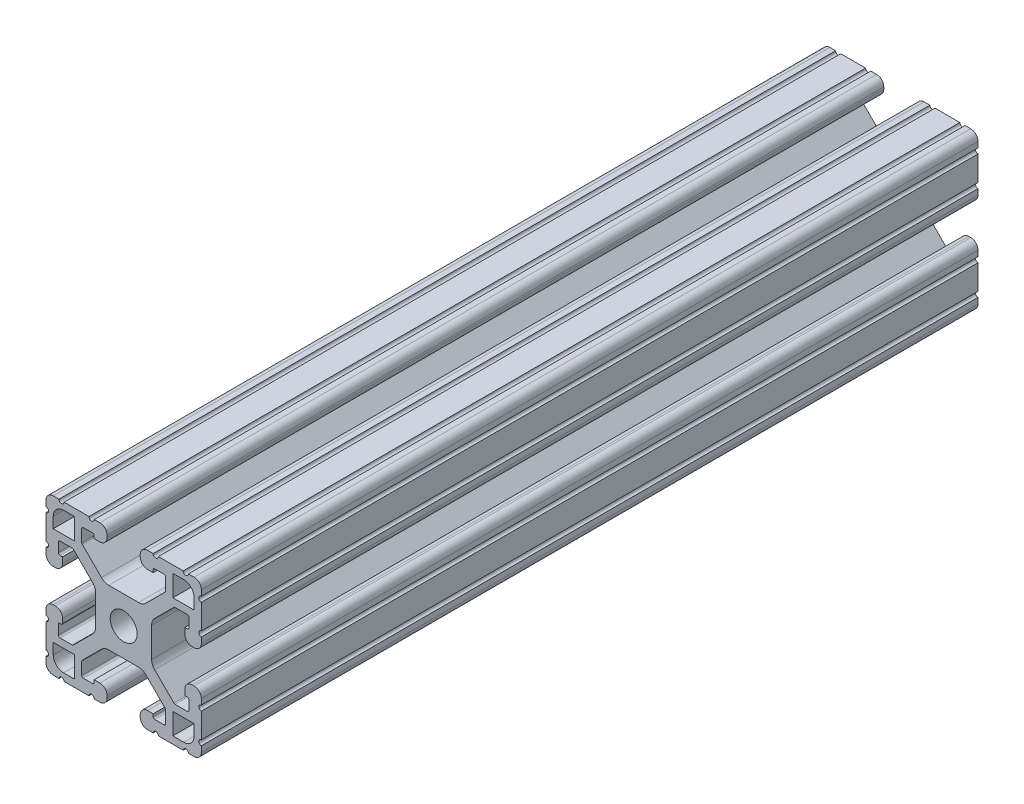
SolidWorks part; units mm, degrees
ref_plane "Front Plane" through (0, 0, 0) normal (0, 0, 1) x (1, 0, 0)
ref_plane "Top Plane" through (0, 0, 0) normal (0, 1, 0) x (1, 0, 0)
ref_plane "Right Plane" through (0, 0, 0) normal (1, 0, 0) x (0, 0, -1)
sketch "Sketch1" plane through (0, 0, 0) normal (0, 0, 1) x (1, 0, 0)
  line L0 (0, -19.05) -> (0, 19.05) construction
  line L1 (19.05, 0) -> (-19.05, 0) construction
  line L2 (4.064, 19.05) -> (-4.064, 19.05) construction
  line L3 (0, -6.858) -> (0, 6.858) construction
  line L4 (-4.064, 19.05) -> (-4.064, 14.986) construction
  line L5 (19.05, -10.287) -> (19.05, 10.287) construction
  line L6 (0, -3.302) -> (0, 3.302) construction
  point P4 (0, 0)
  point P8 (0, 0)
  point P11 (0, 19.05)
  point P14 (0, 0)
  point P18 (19.05, 0)
  point P21 (0, 0)
  dimension "Rail Width" = 38.1
  dimension "Rail Height" = 38.1
  dimension "T-Slot Width" = 8.128
  dimension "Thickness" = 4.064
  dimension "Opening Width" = 20.574
  dimension "Center Hole Diameter" = 6.604
  dimension "Slot Depth" = 12.192
sketch "Sketch2" plane through (0, 0, 0) normal (1, 0, 0) x (0, 0, -1)
  line L0 (-95.25, 0) -> (95.25, 0) construction
  line L1 (0, 19.05) -> (0, -19.05) construction
  line L2 (-25.4, 19.05) -> (25.4, 19.05) construction
  line L4 (3048, -19.05) -> (-3048, -19.05) construction
  point P0 (44.45, 0)
  point P3 (-44.45, 0)
  point P4 (0, 0)
  dimension "D1" = 50.8
  dimension "Rep Length" = 190.5
  dimension "D2" = 50.8
  dimension "Length Range [Min]" = 50.8
  dimension "Length Range [Max]" = 6096
sketch "Sketch3" plane through (0, 0, 0) normal (0, 0, 1) x (1, 0, 0)
  line L1 (19.05, -19.05) -> (-19.05, -19.05)
  line L2 (19.05, -19.05) -> (19.05, 19.05)
  line L3 (19.05, 19.05) -> (-19.05, 19.05)
  line L4 (-19.05, -19.05) -> (-19.05, 19.05)
  line L5 (19.05, -19.05) -> (-19.05, 19.05) construction
  line L6 (19.05, 19.05) -> (-19.05, -19.05) construction
  point P0 (0, 0)
extrude "Boss-Extrude1" add sketch "Sketch3" along normal up to vertex (95.25 mm away) and the other way up to vertex (95.25 mm away) up to point (0, 0, 95.25) other way up to point (0, 0, -95.25)
sketch "Sketch4" plane through (0, 0, 95.25) normal (0, 0, 1) x (1, 0, 0)
  line L4 (4.064, 14.986) -> (4.064, 19.05)
  line L5 (7.239, 14.986) -> (4.064, 14.986)
  line L6 (19.05, 0) -> (-19.05, 0) construction
  line L7 (4.7027, 6.858) -> (-4.7027, 6.858)
  line L8 (-4.7027, 6.858) -> (-10.287, 12.4423)
  line L37 (-19.05, 19.05) -> (-19.05, -19.05) construction
  line L38 (-19.05, -19.05) -> (19.05, -19.05) construction
  line L39 (-10.287, 12.4423) -> (-10.287, 16.002)
  line L40 (-10.287, 16.002) -> (-7.239, 16.002)
  line L41 (-7.239, 16.002) -> (-7.239, 14.986)
  line L42 (-7.239, 14.986) -> (-4.064, 14.986)
  line L43 (-4.064, 14.986) -> (-4.064, 19.05)
  line L44 (-4.064, 19.05) -> (4.064, 19.05)
  line L45 (0, 19.05) -> (0, 0) construction
  line L46 (-19.05, 19.05) -> (0, 0) construction
  line L47 (7.239, 16.002) -> (7.239, 14.986)
  line L48 (10.287, 16.002) -> (7.239, 16.002)
  line L49 (10.287, 12.4423) -> (10.287, 16.002)
  line L50 (4.7027, 6.858) -> (10.287, 12.4423)
  line L51 (-19.05, 0) -> (19.05, 0) construction
  line L52 (4.7027, -6.858) -> (10.287, -12.4423)
  line L53 (10.287, -12.4423) -> (10.287, -16.002)
  line L54 (10.287, -16.002) -> (7.239, -16.002)
  line L55 (7.239, -16.002) -> (7.239, -14.986)
  line L56 (-4.064, -19.05) -> (4.064, -19.05)
  line L57 (-4.064, -14.986) -> (-4.064, -19.05)
  line L58 (-7.239, -14.986) -> (-4.064, -14.986)
  line L59 (-7.239, -16.002) -> (-7.239, -14.986)
  line L60 (-10.287, -16.002) -> (-7.239, -16.002)
  line L61 (-10.287, -12.4423) -> (-10.287, -16.002)
  line L62 (-4.7027, -6.858) -> (-10.287, -12.4423)
  line L63 (4.7027, -6.858) -> (-4.7027, -6.858)
  line L64 (7.239, -14.986) -> (4.064, -14.986)
  line L65 (4.064, -14.986) -> (4.064, -19.05)
  line L66 (-6.858, -4.7027) -> (-12.4423, -10.287)
  line L67 (-12.4423, -10.287) -> (-16.002, -10.287)
  line L68 (-16.002, -10.287) -> (-16.002, -7.239)
  line L69 (-16.002, -7.239) -> (-14.986, -7.239)
  line L70 (-19.05, 4.064) -> (-19.05, -4.064)
  line L71 (-14.986, 4.064) -> (-19.05, 4.064)
  line L72 (-14.986, 7.239) -> (-14.986, 4.064)
  line L73 (-16.002, 7.239) -> (-14.986, 7.239)
  line L74 (-16.002, 10.287) -> (-16.002, 7.239)
  line L75 (-12.4423, 10.287) -> (-16.002, 10.287)
  line L76 (-6.858, 4.7027) -> (-12.4423, 10.287)
  line L77 (-6.858, -4.7027) -> (-6.858, 4.7027)
  line L78 (-14.986, -7.239) -> (-14.986, -4.064)
  line L79 (-14.986, -4.064) -> (-19.05, -4.064)
  line L80 (14.986, -4.064) -> (19.05, -4.064)
  line L81 (14.986, -7.239) -> (14.986, -4.064)
  line L82 (6.858, -4.7027) -> (6.858, 4.7027)
  line L83 (6.858, 4.7027) -> (12.4423, 10.287)
  line L84 (12.4423, 10.287) -> (16.002, 10.287)
  line L85 (16.002, 10.287) -> (16.002, 7.239)
  line L86 (16.002, 7.239) -> (14.986, 7.239)
  line L87 (14.986, 7.239) -> (14.986, 4.064)
  line L88 (14.986, 4.064) -> (19.05, 4.064)
  line L89 (19.05, 4.064) -> (19.05, -4.064)
  line L90 (16.002, -7.239) -> (14.986, -7.239)
  line L91 (16.002, -10.287) -> (16.002, -7.239)
  line L92 (12.4423, -10.287) -> (16.002, -10.287)
  line L93 (6.858, -4.7027) -> (12.4423, -10.287)
  line L94 (19.05, -19.05) -> (19.05, 19.05) construction
  line L95 (12.065, 17.272) -> (17.272, 17.272)
  line L96 (12.065, 17.272) -> (12.065, 12.065)
  line L97 (12.065, 12.065) -> (17.272, 12.065)
  line L98 (17.272, 17.272) -> (17.272, 12.065)
  line L99 (19.05, 19.05) -> (-19.05, 19.05) construction
  line L100 (17.272, -17.272) -> (17.272, -12.065)
  line L101 (12.065, -17.272) -> (17.272, -17.272)
  line L102 (12.065, -17.272) -> (12.065, -12.065)
  line L103 (12.065, -12.065) -> (17.272, -12.065)
  line L104 (-17.272, 17.272) -> (-17.272, 12.065)
  line L105 (-12.065, 12.065) -> (-17.272, 12.065)
  line L106 (-12.065, 17.272) -> (-12.065, 12.065)
  line L107 (-12.065, 17.272) -> (-17.272, 17.272)
  line L108 (-12.065, -12.065) -> (-17.272, -12.065)
  line L109 (-12.065, -17.272) -> (-12.065, -12.065)
  line L110 (-12.065, -17.272) -> (-17.272, -17.272)
  line L111 (-17.272, -17.272) -> (-17.272, -12.065)
  circle A5 centre (0, 0) radius 3.302
  point P21 (0, 6.858)
  point P23 (0, -6.858)
  point P38 (-6.858, 0)
  point P53 (6.858, 0)
  dimension "D1" = 20.574
  dimension "D2" = 3.048
  dimension "D3" = 3.048
  dimension "D4" = 3.048
  dimension "D5" = 1.778
  dimension "D6" = 1.778
  dimension "D7" = 1.778
extrude "Cut-Extrude1" cut sketch "Sketch4" against normal through all
sketch "Sketch5" plane through (0, 0, 95.25) normal (0, 0, 1) x (1, 0, 0)
  line L4 (-4.064, 19.05) -> (-19.05, 19.05) construction
  line L26 (-19.05, 19.05) -> (-19.05, 4.064) construction
  line L27 (-15.875, 19.05) -> (-14.605, 19.05)
  line L28 (-8.509, 19.05) -> (-7.239, 19.05)
  line L29 (-19.05, 15.875) -> (-19.05, 14.605)
  line L30 (-19.05, 8.509) -> (-19.05, 7.239)
  line L31 (8.509, 19.05) -> (7.239, 19.05)
  line L32 (15.875, 19.05) -> (14.605, 19.05)
  line L33 (19.05, 15.875) -> (19.05, 14.605)
  line L34 (19.05, 8.509) -> (19.05, 7.239)
  line L35 (19.05, -8.509) -> (19.05, -7.239)
  line L36 (19.05, -15.875) -> (19.05, -14.605)
  line L37 (15.875, -19.05) -> (14.605, -19.05)
  line L38 (8.509, -19.05) -> (7.239, -19.05)
  line L39 (-8.509, -19.05) -> (-7.239, -19.05)
  line L40 (-15.875, -19.05) -> (-14.605, -19.05)
  line L41 (-19.05, -15.875) -> (-19.05, -14.605)
  line L42 (-19.05, -8.509) -> (-19.05, -7.239)
  line L43 (19.05, 19.05) -> (4.064, 19.05) construction
  line L44 (19.05, 4.064) -> (19.05, 19.05) construction
  line L48 (-14.986, 4.064) -> (-19.05, 4.064) construction
  line L49 (-4.064, 14.986) -> (-4.064, 19.05) construction
  arc A8 (-15.875, 19.05) -> (-14.605, 19.05) centre (-15.24, 19.05) ccw
  arc A9 (-8.509, 19.05) -> (-7.239, 19.05) centre (-7.874, 19.05) ccw
  arc A10 (-19.05, 14.605) -> (-19.05, 15.875) centre (-19.05, 15.24) ccw
  arc A11 (-19.05, 7.239) -> (-19.05, 8.509) centre (-19.05, 7.874) ccw
  arc A12 (7.239, 19.05) -> (8.509, 19.05) centre (7.874, 19.05) ccw
  arc A13 (14.605, 19.05) -> (15.875, 19.05) centre (15.24, 19.05) ccw
  arc A14 (19.05, 15.875) -> (19.05, 14.605) centre (19.05, 15.24) ccw
  arc A15 (19.05, 8.509) -> (19.05, 7.239) centre (19.05, 7.874) ccw
  arc A16 (19.05, -7.239) -> (19.05, -8.509) centre (19.05, -7.874) ccw
  arc A17 (19.05, -14.605) -> (19.05, -15.875) centre (19.05, -15.24) ccw
  arc A18 (15.875, -19.05) -> (14.605, -19.05) centre (15.24, -19.05) ccw
  arc A19 (8.509, -19.05) -> (7.239, -19.05) centre (7.874, -19.05) ccw
  arc A20 (-7.239, -19.05) -> (-8.509, -19.05) centre (-7.874, -19.05) ccw
  arc A21 (-14.605, -19.05) -> (-15.875, -19.05) centre (-15.24, -19.05) ccw
  arc A22 (-19.05, -15.875) -> (-19.05, -14.605) centre (-19.05, -15.24) ccw
  arc A23 (-19.05, -8.509) -> (-19.05, -7.239) centre (-19.05, -7.874) ccw
  dimension "D2" = 0.635
  dimension "D4" = 3.81
  dimension "D5" = 3.81
  dimension "D1" = 3.81
  dimension "D3" = 3.81
  dimension "D7" = 4
extrude "Cut-Extrude2" cut sketch "Sketch5" against normal through all
fillet "Fillet1" radius 2.54 12 edges at (-6.858, 4.7027, 0) (-6.858, -4.7027, 0) (4.7027, -6.858, 0) (-4.7027, -6.858, 0) (6.858, -4.7027, 0) (6.858, 4.7027, 0) (4.7027, 6.858, 0) (-4.7027, 6.858, 0) (-17.272, 17.272, 0) (17.272, 17.272, 0) (17.272, -17.272, 0) (-17.272, -17.272, 0)
fillet "Fillet2" radius 1.778 20 edges at (19.05, -19.05, 0) (19.05, 19.05, 0) (-19.05, -19.05, 0) (-19.05, 19.05, 0) (-14.986, 4.064, 0) (-19.05, 4.064, 0) (-19.05, -4.064, 0) (-14.986, -4.064, 0) (-4.064, -19.05, 0) (-4.064, -14.986, 0) (4.064, -14.986, 0) (4.064, -19.05, 0) (19.05, -4.064, 0) (14.986, -4.064, 0) (19.05, 4.064, 0) (14.986, 4.064, 0) (4.064, 14.986, 0) (4.064, 19.05, 0) (-4.064, 19.05, 0) (-4.064, 14.986, 0)
fillet "Fillet3" radius 0.3969 24 edges at (-14.986, -7.239, 0) (-16.002, -10.287, 0) (-12.4423, -10.287, 0) (-12.4423, 10.287, 0) (-16.002, 7.239, 0) (-16.002, 10.287, 0) (-10.287, 12.4423, 0) (-7.239, 16.002, 0) (-10.287, 16.002, 0) (10.287, 16.002, 0) (7.239, 16.002, 0) (10.287, 12.4423, 0) (16.002, 10.287, 0) (12.4423, 10.287, 0) (16.002, 7.239, 0) (16.002, -7.239, 0) (16.002, -10.287, 0) (12.4423, -10.287, 0) (10.287, -12.4423, 0) (10.287, -16.002, 0) (7.239, -16.002, 0) (-7.239, -16.002, 0) (-10.287, -12.4423, 0) (-10.287, -16.002, 0)
equation "\"D4@Sketch5\"=\"D3@Sketch5\""
equation "\"D5@Sketch5\"=\"D4@Sketch5\""
equation "\"D1@Sketch4\"=\"Opening Width@Sketch1\""
